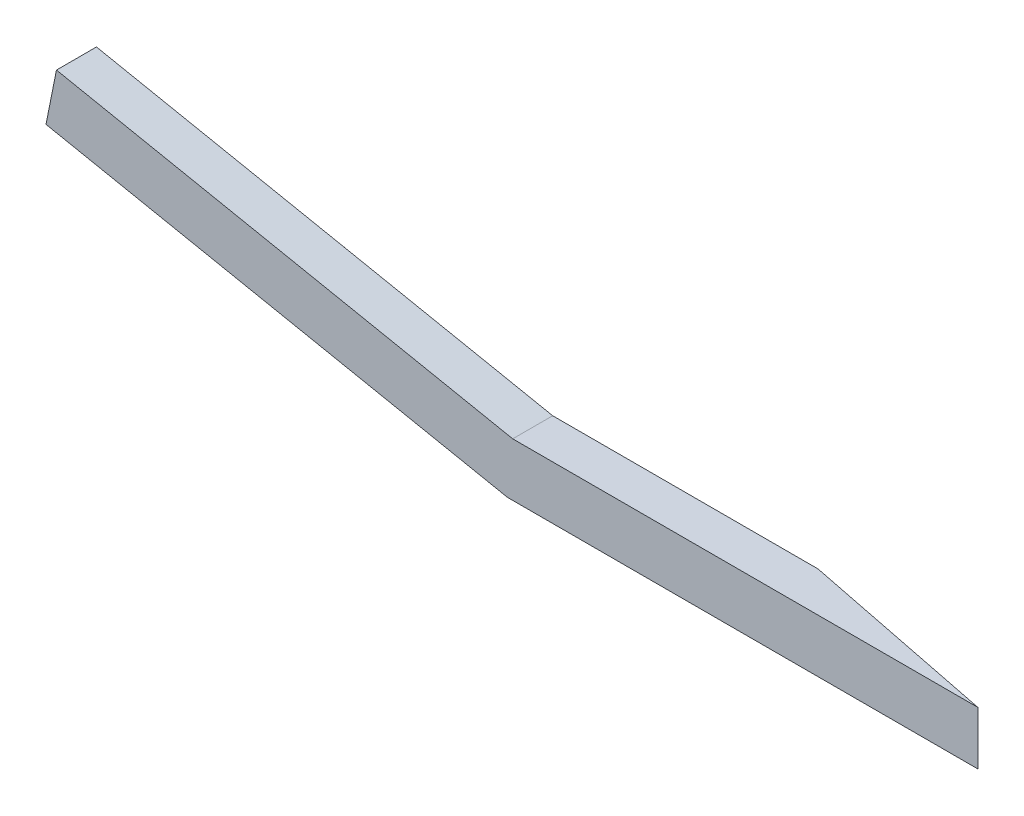
SolidWorks part; units mm, degrees
ref_plane "Front Plane" through (0, 0, 0) normal (0, 0, 1) x (1, 0, 0)
ref_plane "Top Plane" through (0, 0, 0) normal (0, 1, 0) x (1, 0, 0)
ref_plane "Right Plane" through (0, 0, 0) normal (1, 0, 0) x (0, 0, -1)
sketch "Sketch1" plane through (0, 0, 0) normal (0, 1, 0) x (1, 0, 0)
  line L0 (-1.8787, -1.397) -> (-1.8787, -0.1223)
  line L1 (-1.8787, -0.1223) -> (6.7475, -0.1223)
  line L5 (6.7475, -0.1223) -> (13.1213, -1.397)
  line L6 (13.1213, -1.397) -> (-1.8787, -1.397)
extrude "Boss-Extrude2" add sketch "Sketch1" along normal blind 1.7
sketch "Sketch4" plane through (0, 0, 1.397) normal (0, 0, 1) x (1, 0, 0)
  line L0 (-1.8787, 0) -> (-16.5874, 2.9417)
  line L1 (-16.5874, 2.9417) -> (-16.254, 4.6087)
  line L2 (-16.254, 4.6087) -> (-1.5453, 1.667)
  line L3 (-1.5453, 1.667) -> (-1.8787, 0)
extrude "Boss-Extrude4" add sketch "Sketch4" against normal up to vertex (1.2748 mm away)
